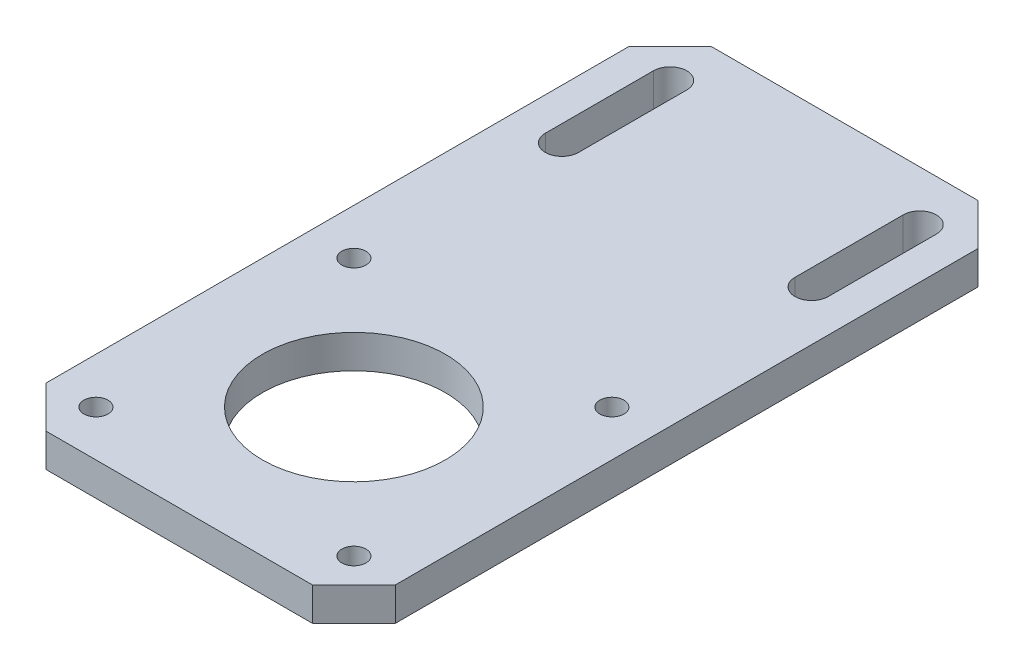
SolidWorks part; units mm, degrees
ref_plane "前视基准面" through (0, 0, 0) normal (0, 0, 1) x (1, 0, 0)
ref_plane "上视基准面" through (0, 0, 0) normal (0, 1, 0) x (1, 0, 0)
ref_plane "右视基准面" through (0, 0, 0) normal (1, 0, 0) x (0, 0, -1)
sketch "草图1" plane through (0, 0, 0) normal (0, 1, 0) x (1, 0, 0)
  line L0 (6, 74) -> (6, 61) construction
  line L1 (0, 0) -> (42, 0)
  line L2 (0, 0) -> (0, 80)
  line L3 (0, 80) -> (42, 80)
  line L4 (42, 0) -> (42, 80)
  line L5 (8, 74) -> (8, 61)
  line L6 (4, 74) -> (4, 61)
  line L7 (36, 74) -> (36, 61) construction
  line L8 (38, 74) -> (38, 61)
  line L9 (34, 74) -> (34, 61)
  circle A0 centre (21, 21) radius 11
  circle A1 centre (5.5, 36.5) radius 1.45
  circle A2 centre (5.5, 5.5) radius 1.45
  circle A3 centre (36.5, 36.5) radius 1.45
  circle A4 centre (36.5, 5.5) radius 1.45
  arc A5 (8, 74) -> (4, 74) centre (6, 74) ccw
  arc A6 (4, 61) -> (8, 61) centre (6, 61) ccw
  arc A7 (38, 74) -> (34, 74) centre (36, 74) ccw
  arc A8 (34, 61) -> (38, 61) centre (36, 61) ccw
  point P15 (6, 67.5)
  point P20 (21, 0)
  point P23 (36, 67.5)
  dimension "D6" = 22
  dimension "D7" = 2.9
  dimension "D12" = 2
  dimension "D1" = 42
  dimension "D2" = 31
  dimension "D3" = 31
  dimension "D4" = 5.5
  dimension "D5" = 21
  dimension "D8" = 5.5
  dimension "D9" = 80
  dimension "D10" = 30
  dimension "D11" = 6
  dimension "D13" = 40
  dimension "D14" = 13
extrude "凸台-拉伸1" add sketch "草图1" along normal blind 4
chamfer "倒角1" distance 5 angle 45 4 edges at (42, 2, -80) (0, 2, -80) (0, 2, 0) (42, 2, 0)
